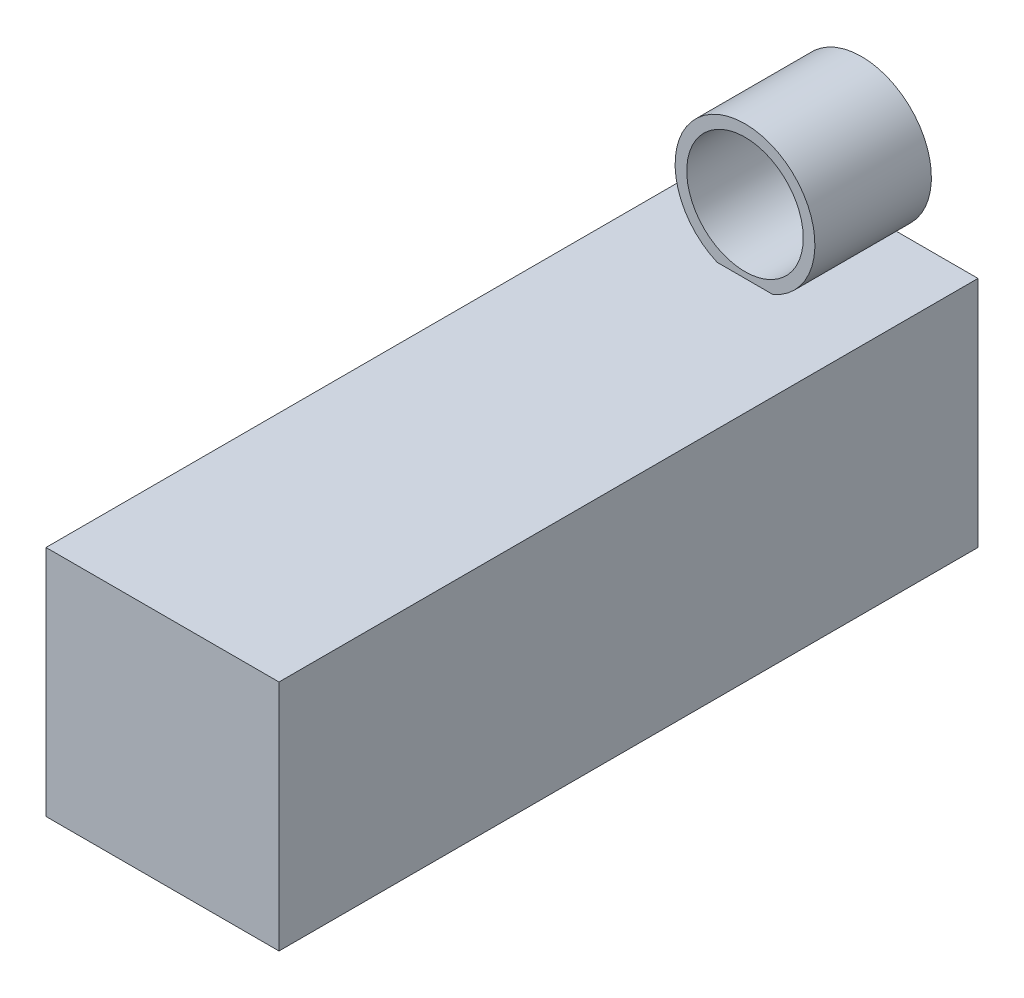
SolidWorks part; units mm, degrees
ref_plane "Front Plane" through (0, 0, 0) normal (0, 0, 1) x (1, 0, 0)
ref_plane "Top Plane" through (0, 0, 0) normal (0, 1, 0) x (1, 0, 0)
ref_plane "Right Plane" through (0, 0, 0) normal (1, 0, 0) x (0, 0, -1)
sketch "Sketch1" plane through (0, 0, 0) normal (0, 0, 1) x (1, 0, 0)
  line L1 (0, 0) -> (20, 0)
  line L2 (0, 0) -> (0, -20)
  line L3 (0, -20) -> (20, -20)
  line L4 (20, 0) -> (20, -20)
  dimension "D1" = 20
  dimension "D2" = 20
extrude "Boss-Extrude1" add sketch "Sketch1" along normal blind 60
sketch "Sketch2" plane through (0, -20, 0) normal (0, -1, 0) x (1, 0, 0)
  line L0 (0, 60) -> (20, 60) construction
  line L1 (20, 60) -> (20, 0) construction
  circle A0 centre (10, 30) radius 2.6
  dimension "D1" = 30
  dimension "D3" = 5.2
  dimension "D2" = 10
extrude "Cut-Extrude1" cut sketch "Sketch2" against normal blind 5
sketch "Sketch3" plane through (0, 0, 0) normal (0, 0, 1) x (1, 0, 0)
  line L0 (20, 0) -> (0, 0) construction
  line L1 (0, 0) -> (0, -20) construction
  circle A0 centre (10, 5.5) radius 5
  circle A1 centre (10, 5.5) radius 6
  point P3 (9.5001, 6.5503)
  point P8 (-28.1509, 15.9092)
  dimension "D1" = 10
  dimension "D2" = 12
  dimension "D3" = 5.5
  dimension "D4" = 10
extrude "Boss-Extrude2" add sketch "Sketch3" along normal blind 10
